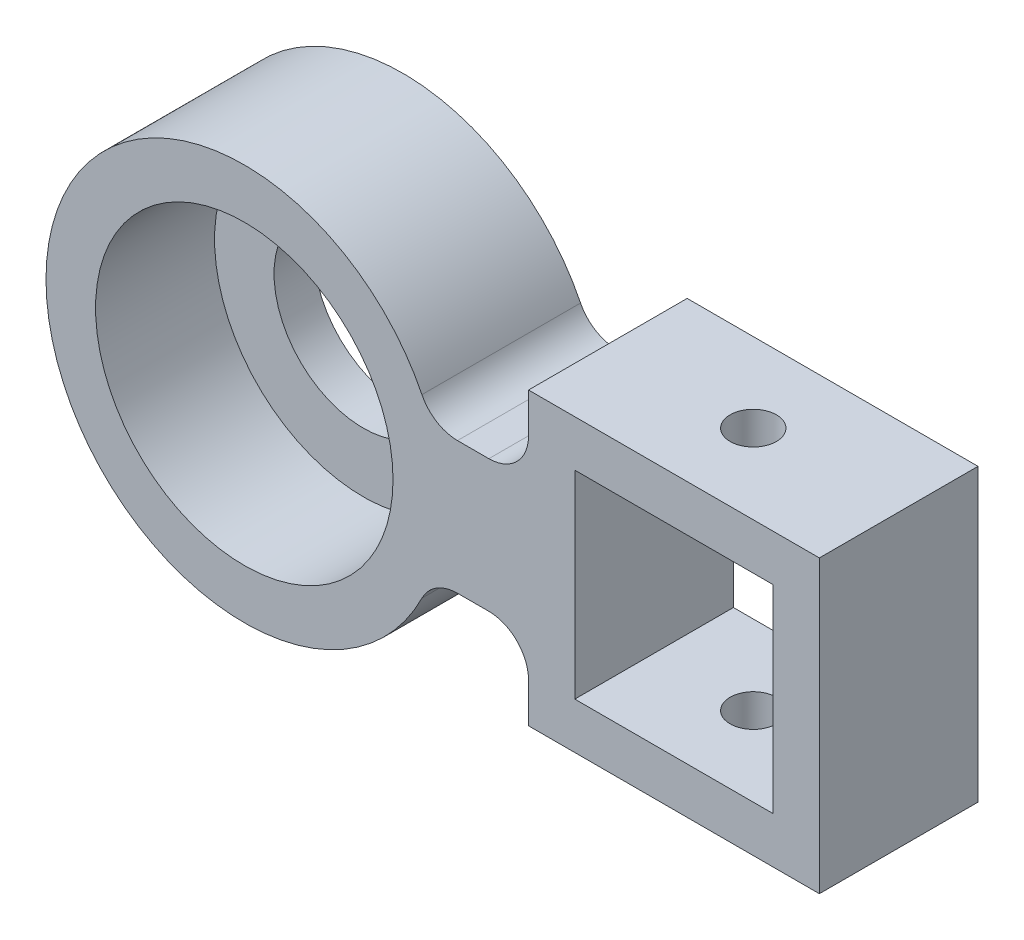
SolidWorks part; units mm, degrees
ref_plane "Front Plane" through (0, 0, 0) normal (0, 0, 1) x (1, 0, 0)
ref_plane "Top Plane" through (0, 0, 0) normal (0, 1, 0) x (1, 0, 0)
ref_plane "Right Plane" through (0, 0, 0) normal (1, 0, 0) x (0, 0, -1)
sketch "Sketch1" plane through (0, 0, 0) normal (0, 0, 1) x (1, 0, 0)
  line L0 (-15.3689, 3.9028) -> (-40.3689, 3.9028) construction
  line L1 (-15.3689, 11.4028) -> (-0.3689, 11.4028)
  line L2 (-15.3689, 11.4028) -> (-15.3689, -3.5972)
  line L3 (-15.3689, -3.5972) -> (-0.3689, -3.5972)
  line L4 (-0.3689, 11.4028) -> (-0.3689, -3.5972)
  line L5 (-18.8689, 14.9028) -> (3.1311, 14.9028)
  line L6 (-18.8689, 14.9028) -> (-18.8689, 8.9028)
  line L7 (-18.8689, -7.0972) -> (3.1311, -7.0972)
  line L8 (3.1311, 14.9028) -> (3.1311, -7.0972)
  line L9 (-26.2268, -1.0972) -> (-18.8689, -1.0972)
  line L10 (-26.2268, 8.9028) -> (-18.8689, 8.9028)
  line L11 (-18.8689, -1.0972) -> (-18.8689, -7.0972)
  circle A0 centre (-40.3689, 3.9028) radius 6.75
  circle A1 centre (-40.3689, 3.9028) radius 11 construction
  arc A2 (-26.2268, 8.9028) -> (-26.2268, -1.0972) centre (-40.3689, 3.9028) ccw
  dimension "D6" = 13.5
  dimension "D7" = 22
  dimension "D8" = 4
  dimension "D1" = 15
  dimension "D2" = 3.5
  dimension "D3" = 3.5
  dimension "D4" = 3.5
  dimension "D5" = 3.5
  dimension "D9" = 10
  dimension "D10" = 5
  dimension "D11" = 25
extrude "Boss-Extrude1" add sketch "Sketch1" along normal blind 12
sketch "Sketch2" plane through (0, -7.0972, 0) normal (0, -1, 0) x (1, 0, 0)
  line L0 (-7.8689, 12) -> (-7.8689, 0) construction
  line L1 (-18.8689, 12) -> (3.1311, 12) construction
  line L2 (-18.8689, 0) -> (3.1311, 0) construction
  line L3 (3.1311, 6) -> (-18.8689, 6) construction
  line L4 (3.1311, 12) -> (3.1311, 0) construction
  line L5 (-18.8689, 12) -> (-18.8689, 0) construction
  circle A0 centre (-7.8689, 6) radius 1.75
  dimension "D1" = 3.5
extrude "Cut-Extrude1" cut sketch "Sketch2" against normal up to surface (22 mm away) up to face at (-7.8689, 14.9028, 6)
fillet "Fillet1" radius 3 4 edges at (-18.8689, -1.0972, 6) (-18.8689, 8.9028, 6) (-26.2268, 8.9028, 6) (-26.2268, -1.0972, 6)
sketch "Sketch3" plane through (0, 0, 12) normal (0, 0, 1) x (1, 0, 0)
  circle A0 centre (-40.3689, 3.9028) radius 11.25
  dimension "D1" = 22.5
extrude "Cut-Extrude2" cut sketch "Sketch3" against normal offset from surface (9 mm away) 3 up to face at (-7.8689, 3.9028, 0)
